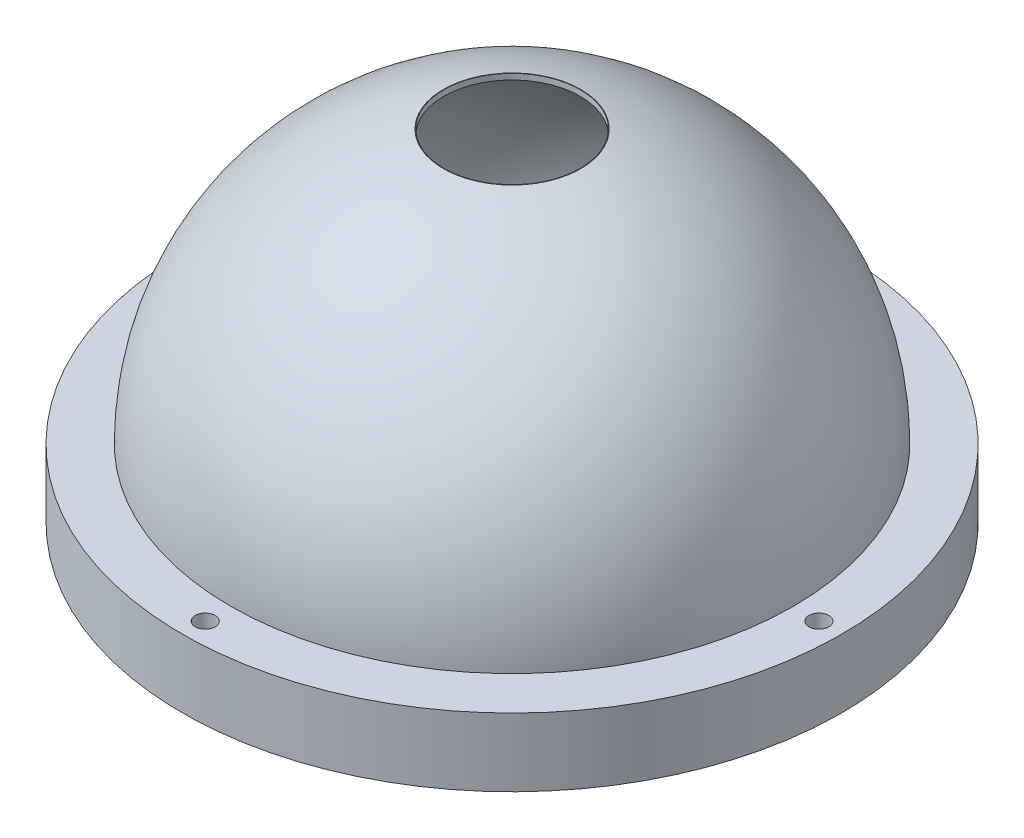
SolidWorks part; units mm, degrees
ref_plane "Front Plane" through (0, 0, 0) normal (0, 0, 1) x (1, 0, 0)
ref_plane "Top Plane" through (0, 0, 0) normal (0, 1, 0) x (1, 0, 0)
ref_plane "Right Plane" through (0, 0, 0) normal (1, 0, 0) x (0, 0, -1)
sketch "Sketch1" plane through (0, 0, 0) normal (0, 0, 1) x (1, 0, 0)
  line L0 (0, -100.5382) -> (0, 66.1215) construction
  line L1 (0, 0) -> (48.5, 0) construction
  line L3 (0, 47) -> (11.9687, 47)
  arc A0 (48.5, 0) -> (11.9687, 47) centre (0, 0) ccw
  point P7 (0, -17.2083)
  dimension "D1" = 47
  dimension "D2" = 48.5
revolve "Revolve-Thin1" add sketch "Sketch1" angle 360 about L0 wall 1
sketch "Sketch2" plane through (0, 48, 0) normal (0, 1, 0) x (1, 0, 0)
  circle A0 centre (0, 0) radius 12
  dimension "D1" = 24
extrude "Cut-Extrude1" cut sketch "Sketch2" against normal up to next
sketch "Sketch3" plane through (0, 0, 0) normal (0, -1, 0) x (1, 0, 0)
  circle A0 centre (0, 0) radius 48.5
  circle A1 centre (0, 0) radius 58
  dimension "D1" = 116
  dimension "D2" = 97
extrude "Boss-Extrude1" add sketch "Sketch3" along normal blind 12
sketch "Sketch4" plane through (0, -12, 0) normal (0, -1, 0) x (1, 0, 0)
  line L0 (0, 54) -> (0, -54) construction
  line L1 (54, 0) -> (-54, 0) construction
  circle A0 centre (0, 0) radius 54 construction
  circle A1 centre (0, 54) radius 1.75
  circle A5 centre (54, 0) radius 1.75
  circle A6 centre (-54, 0) radius 1.75
  circle A7 centre (0, -54) radius 1.75
  point P14 (0, 0)
  dimension "D1" = 108
  dimension "D2" = 3.5
extrude "Cut-Extrude2" cut sketch "Sketch4" against normal up to next
